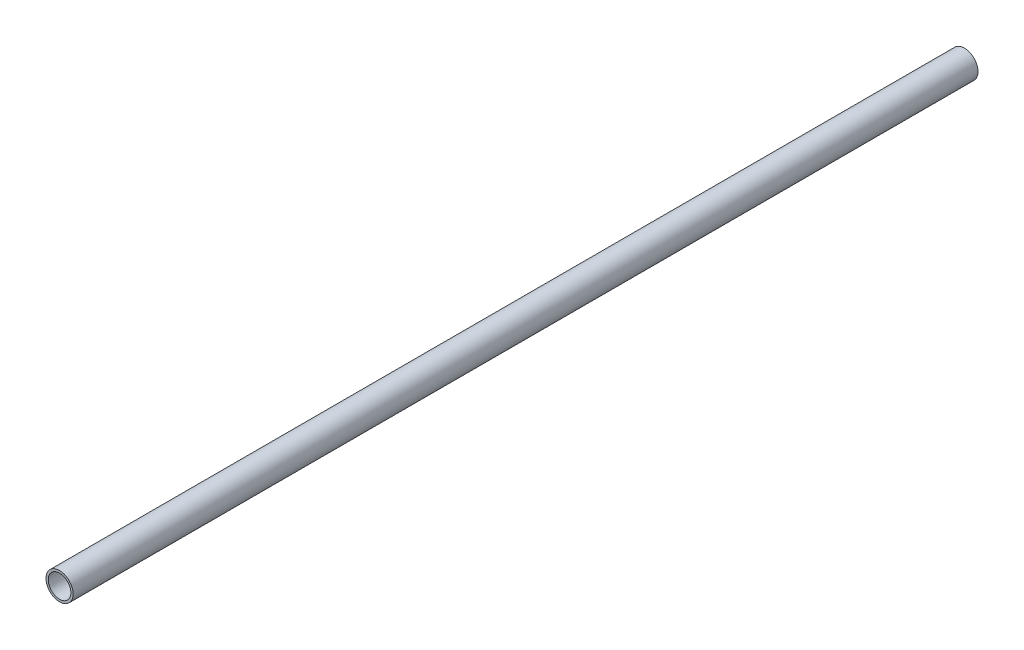
SolidWorks part; units mm, degrees
material "Laiton"
ref_plane "Plan de face" through (0, 0, 0) normal (0, 0, 1) x (1, 0, 0)
ref_plane "Plan de dessus" through (0, 0, 0) normal (0, 1, 0) x (1, 0, 0)
ref_plane "Plan de droite" through (0, 0, 0) normal (1, 0, 0) x (0, 0, -1)
sketch "Esquisse1" plane through (0, 0, 0) normal (0, 0, 1) x (1, 0, 0)
  circle A0 centre (0, 0) radius 2.5
  circle A1 centre (0, 0) radius 3
  dimension "D1" = 5
  dimension "D2" = 6
extrude "Boss.-Extru.1" add sketch "Esquisse1" along normal blind 200
